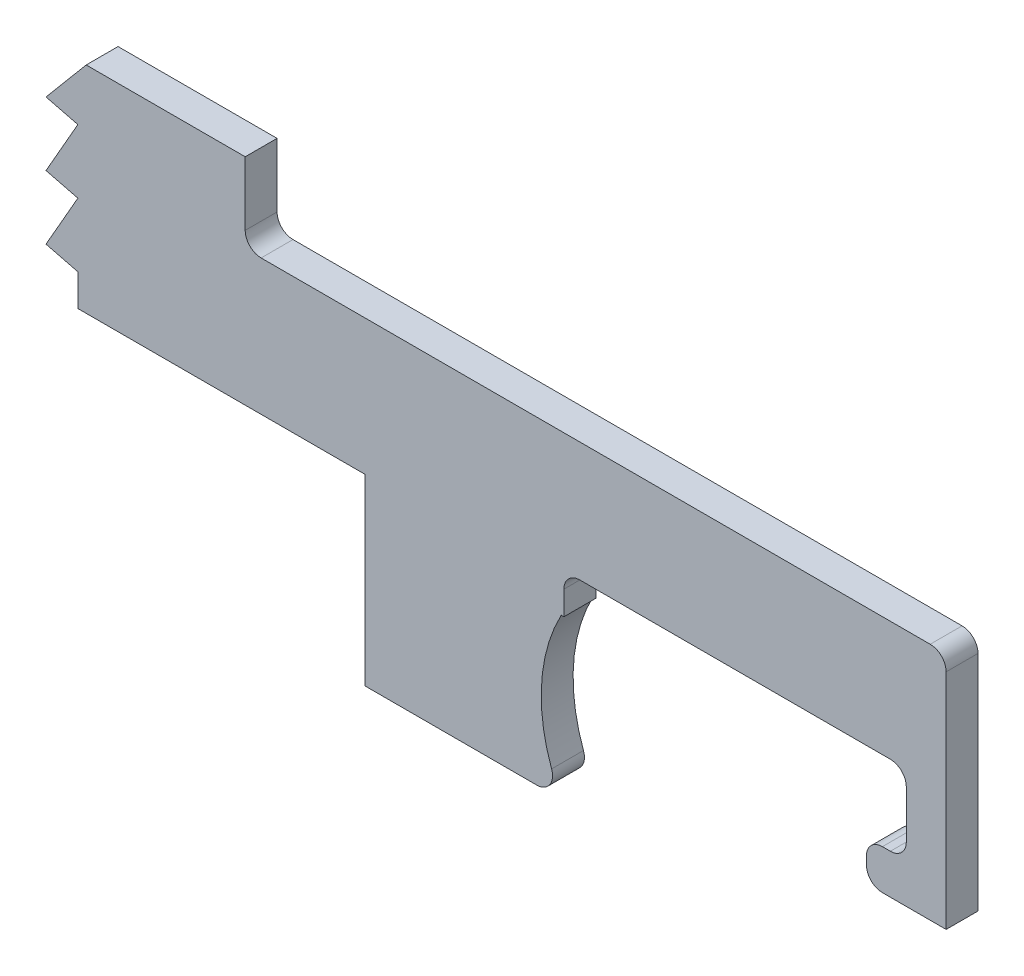
SolidWorks part; units mm, degrees
ref_plane "Front Plane" through (0, 0, 0) normal (0, 0, 1) x (1, 0, 0)
ref_plane "Top Plane" through (0, 0, 0) normal (0, 1, 0) x (1, 0, 0)
ref_plane "Right Plane" through (0, 0, 0) normal (1, 0, 0) x (0, 0, -1)
sketch "Sketch1" plane through (0, 0, 0) normal (0, 0, 1) x (1, 0, 0)
  line L0 (75.7963, 15) -> (75.7963, -15)
  line L2 (75.7377, 15) -> (-12.1763, 15) construction
  line L3 (-12.1763, 15) -> (75.7963, 15)
  line L4 (27.8237, 0) -> (27.8237, -5)
  line L5 (75.7963, -15) -> (65.7963, -15)
  line L6 (65.7963, -15) -> (65.7963, -10)
  line L7 (65.7963, -10) -> (70.7963, -10)
  line L8 (70.7963, -10) -> (70.7963, 0)
  line L9 (27.4893, -25) -> (2.888, -25)
  line L10 (-17.1763, -25) -> (4.2972, -25) construction
  line L11 (2.888, -25) -> (2.888, -2)
  line L12 (27.8237, 0) -> (70.7963, 0)
  line L13 (-12.1763, 15) -> (-12.1763, 25)
  line L14 (37.4049, -5) -> (12.0192, -5) construction
  line L15 (27.4893, -5) -> (27.8237, -5)
  line L16 (-12.1763, 25) -> (-37.1763, 25)
  line L17 (100.8237, 25) -> (-36.7657, 25) construction
  line L18 (-37.1763, 25) -> (-37.1763, -2)
  line L19 (-42.1763, -2) -> (-17.1763, -2) construction
  line L20 (-37.1763, -2) -> (2.888, -2)
  arc A0 (27.4893, -25) -> (27.4893, -5) centre (46.1406, -15) cw
  dimension "D1" = 25
  dimension "D3" = 5
  dimension "D4" = 5
  dimension "D5" = 10
  dimension "D7" = 5
extrude "Boss-Extrude1" add sketch "Sketch1" along normal blind 4
sketch "Sketch2" plane through (0, 0, 4) normal (0, 0, 1) x (1, 0, 0)
  line L0 (-33.1763, 25) -> (-33.1763, -2) construction
  line L1 (-12.1763, 25) -> (-37.1763, 25) construction
  line L2 (-37.1763, -2) -> (2.888, -2) construction
  line L3 (-37.1763, 19) -> (-32.1338, 25)
  line L4 (-37.1763, 25) -> (-37.1763, -2) construction
  line L5 (-37.1763, 19) -> (-33.1763, 18)
  line L6 (-33.1763, 18) -> (-37.1763, 11)
  line L7 (-37.1763, 11) -> (-33.1763, 10)
  line L8 (-33.1763, 10) -> (-37.1763, 3)
  line L9 (-37.1763, 3) -> (-33.1763, 2)
  line L10 (-33.1763, -2.2427) -> (-33.1763, 2)
  line L14 (-32.1338, 25) -> (-32.1338, 30.9087)
  line L15 (-32.1338, 30.9087) -> (-39.4681, 30.9087)
  line L16 (-39.4681, 30.9087) -> (-39.4681, -2.2427)
  line L17 (-39.4681, -2.2427) -> (-33.1763, -2.2427)
  dimension "D1" = 3
  dimension "D2" = 4
  dimension "D3" = 3
  dimension "D4" = 3
extrude "Cut-Extrude1" cut sketch "Sketch2" against normal blind 10
fillet "Fillet1" radius 2 4 edges at (27.4893, -25, 2) (65.7963, -15, 2) (65.7963, -10, 2) (70.7963, -10, 2)
fillet "Fillet2" radius 2 4 edges at (70.7963, 0, 2) (27.8237, 0, 2) (75.7963, 15, 2) (-12.1763, 15, 2)
